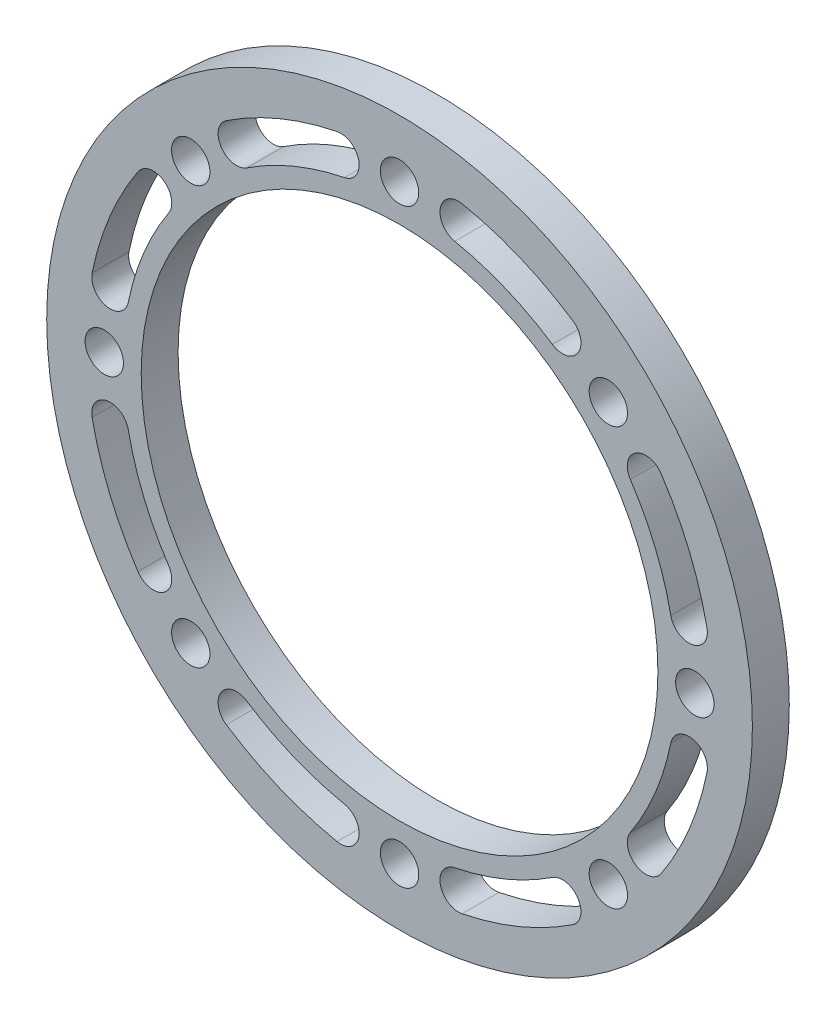
SolidWorks part; units mm, degrees
material "Thornel Mat VMA"
ref_plane "前视基准面" through (0, 0, 0) normal (0, 0, 1) x (1, 0, 0)
ref_plane "上视基准面" through (0, 0, 0) normal (0, 1, 0) x (1, 0, 0)
ref_plane "右视基准面" through (0, 0, 0) normal (1, 0, 0) x (0, 0, -1)
other "Configuration Table"
sketch "草图1" plane through (0, 0, 0) normal (0, 0, 1) x (1, 0, 0)
  circle A0 centre (0, 0) radius 45
  circle A1 centre (0, 0) radius 40 construction
  circle A2 centre (0, 40) radius 2.6 construction
  circle A3 centre (0, 40) radius 2.6
  circle A4 centre (28.2843, 28.2843) radius 2.6
  circle A5 centre (40, 0) radius 2.6
  circle A6 centre (28.2843, -28.2843) radius 2.6
  circle A7 centre (0, -40) radius 2.6
  circle A8 centre (-28.2843, -28.2843) radius 2.6
  circle A9 centre (0, 0) radius 35
  circle A10 centre (-40, 0) radius 2.6
  circle A11 centre (-28.2843, 28.2843) radius 2.6
  point P20 (0, 0)
  dimension "D1" = 90
  dimension "D2" = 5.2
  dimension "D3" = 5
  dimension "D4" = 5.2
  dimension "D6" = 5
  dimension "D5" = 8
extrude "凸台-拉伸2" add sketch "草图1" along normal blind 5
sketch "草图3" plane through (0, 0, 5) normal (0, 0, 1) x (1, 0, 0)
  circle A0 centre (0, 0) radius 47.8
  circle A1 centre (0, 0) radius 45 construction
  circle A2 centre (0, 0) radius 45
  dimension "D1" = 2.8
extrude "凸台-拉伸3" add sketch "草图3" against normal up to surface (5 mm away) up to face at (45, 0, 0)
sketch "草图4" plane through (0, 0, 5) normal (0, 0, 1) x (1, 0, 0)
  line L0 (0, 40) -> (0, 0) construction
  line L1 (0, 0) -> (-7.9747, 39.197) construction
  line L2 (-22.0775, 33.3554) -> (0, 0) construction
  line L3 (-15.3073, 36.9552) -> (0, 0) construction
  circle A0 centre (0, 0) radius 40 construction
  arc A1 (-7.9747, 39.197) -> (-22.0775, 33.3554) centre (0, 0) ccw construction
  arc A2 (-8.4731, 41.6468) -> (-23.4573, 35.4401) centre (0, 0) ccw
  arc A3 (-7.4763, 36.7472) -> (-20.6976, 31.2707) centre (0, 0) ccw
  arc A4 (-7.4763, 36.7472) -> (-8.4731, 41.6468) centre (-7.9747, 39.197) ccw
  arc A5 (-23.4573, 35.4401) -> (-20.6976, 31.2707) centre (-22.0775, 33.3554) ccw
  arc A6 (22.0775, 33.3554) -> (7.9747, 39.197) centre (0, 0) ccw construction
  arc A7 (23.4573, 35.4401) -> (8.4731, 41.6468) centre (0, 0) ccw
  arc A8 (20.6976, 31.2707) -> (7.4763, 36.7472) centre (0, 0) ccw
  arc A9 (20.6976, 31.2707) -> (23.4573, 35.4401) centre (22.0775, 33.3554) ccw
  arc A10 (8.4731, 41.6468) -> (7.4763, 36.7472) centre (7.9747, 39.197) ccw
  arc A11 (39.197, 7.9747) -> (33.3554, 22.0775) centre (0, 0) ccw construction
  arc A12 (41.6468, 8.4731) -> (35.4401, 23.4573) centre (0, 0) ccw
  arc A13 (36.7472, 7.4763) -> (31.2707, 20.6976) centre (0, 0) ccw
  arc A14 (36.7472, 7.4763) -> (41.6468, 8.4731) centre (39.197, 7.9747) ccw
  arc A15 (35.4401, 23.4573) -> (31.2707, 20.6976) centre (33.3554, 22.0775) ccw
  arc A16 (33.3554, -22.0775) -> (39.197, -7.9747) centre (0, 0) ccw construction
  arc A17 (35.4401, -23.4573) -> (41.6468, -8.4731) centre (0, 0) ccw
  arc A18 (31.2707, -20.6976) -> (36.7472, -7.4763) centre (0, 0) ccw
  arc A19 (31.2707, -20.6976) -> (35.4401, -23.4573) centre (33.3554, -22.0775) ccw
  arc A20 (41.6468, -8.4731) -> (36.7472, -7.4763) centre (39.197, -7.9747) ccw
  arc A21 (7.9747, -39.197) -> (22.0775, -33.3554) centre (0, 0) ccw construction
  arc A22 (8.4731, -41.6468) -> (23.4573, -35.4401) centre (0, 0) ccw
  arc A23 (7.4763, -36.7472) -> (20.6976, -31.2707) centre (0, 0) ccw
  arc A24 (7.4763, -36.7472) -> (8.4731, -41.6468) centre (7.9747, -39.197) ccw
  arc A25 (23.4573, -35.4401) -> (20.6976, -31.2707) centre (22.0775, -33.3554) ccw
  arc A26 (-22.0775, -33.3554) -> (-7.9747, -39.197) centre (0, 0) ccw construction
  arc A27 (-23.4573, -35.4401) -> (-8.4731, -41.6468) centre (0, 0) ccw
  arc A28 (-20.6976, -31.2707) -> (-7.4763, -36.7472) centre (0, 0) ccw
  arc A29 (-20.6976, -31.2707) -> (-23.4573, -35.4401) centre (-22.0775, -33.3554) ccw
  arc A30 (-8.4731, -41.6468) -> (-7.4763, -36.7472) centre (-7.9747, -39.197) ccw
  arc A31 (-39.197, -7.9747) -> (-33.3554, -22.0775) centre (0, 0) ccw construction
  arc A32 (-41.6468, -8.4731) -> (-35.4401, -23.4573) centre (0, 0) ccw
  arc A33 (-36.7472, -7.4763) -> (-31.2707, -20.6976) centre (0, 0) ccw
  arc A34 (-36.7472, -7.4763) -> (-41.6468, -8.4731) centre (-39.197, -7.9747) ccw
  arc A35 (-35.4401, -23.4573) -> (-31.2707, -20.6976) centre (-33.3554, -22.0775) ccw
  arc A36 (-33.3554, 22.0775) -> (-39.197, 7.9747) centre (0, 0) ccw construction
  arc A37 (-35.4401, 23.4573) -> (-41.6468, 8.4731) centre (0, 0) ccw
  arc A38 (-31.2707, 20.6976) -> (-36.7472, 7.4763) centre (0, 0) ccw
  arc A39 (-31.2707, 20.6976) -> (-35.4401, 23.4573) centre (-33.3554, 22.0775) ccw
  arc A40 (-41.6468, 8.4731) -> (-36.7472, 7.4763) centre (-39.197, 7.9747) ccw
  point P8 (-15.3073, 36.9552)
  point P20 (15.3073, 36.9552)
  point P27 (36.9552, 15.3073)
  point P34 (36.9552, -15.3073)
  point P41 (15.3073, -36.9552)
  point P48 (-15.3073, -36.9552)
  point P55 (-36.9552, -15.3073)
  point P62 (-36.9552, 15.3073)
  point P67 (0, 0)
  dimension "D1" = 22.5
  dimension "D3" = 2.5
  dimension "D2" = 11
  dimension "D4" = 11
  dimension "D5" = 8
extrude "切除-拉伸1" cut sketch "草图4" against normal blind 10
